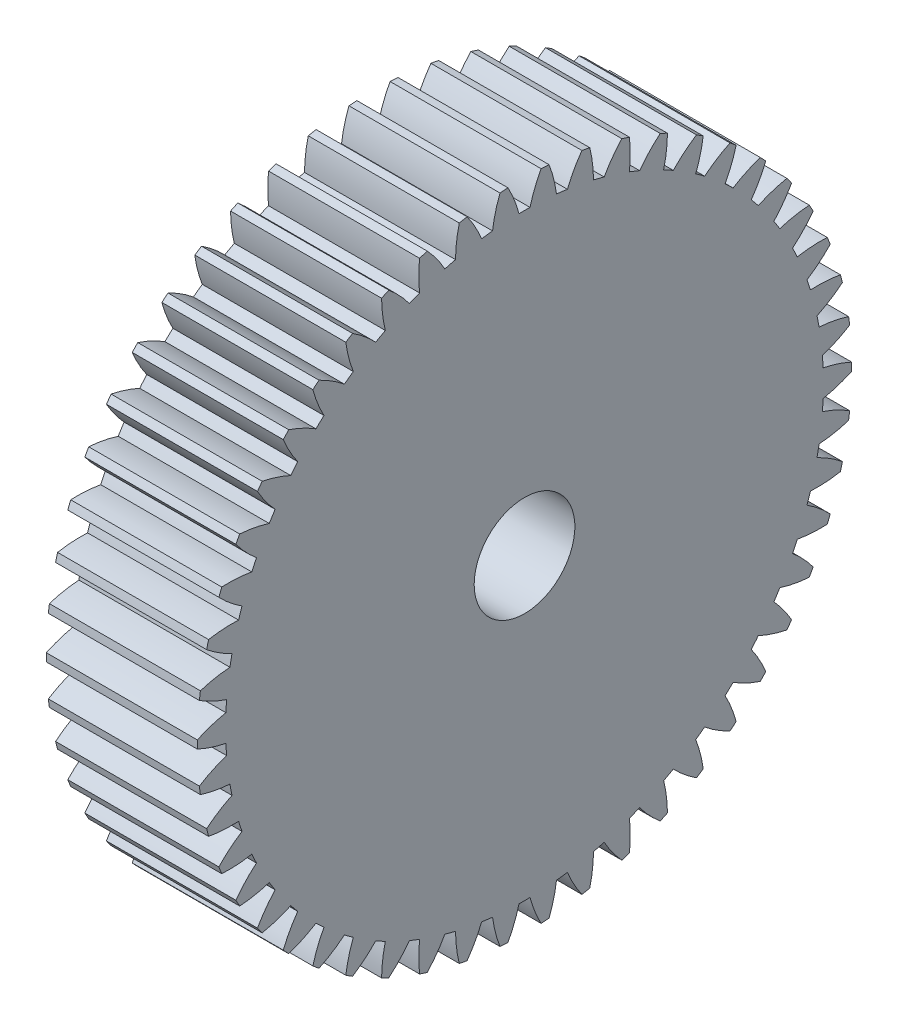
SolidWorks part; units mm, degrees
ref_plane "Plane1" through (0, 0, 0) normal (0, 0, 1) x (1, 0, 0)
ref_plane "Plane2" through (0, 0, 0) normal (0, 1, 0) x (1, 0, 0)
ref_plane "Plane3" through (0, 0, 0) normal (1, 0, 0) x (0, 0, -1)
sketch "HoldingSke" plane through (0, 0, 0) normal (0, 1, 0) x (1, 0, 0)
  line L0 (0, 0) -> (0.6428, -0.766)
  line L1 (-15, 0) -> (100, 0) construction
  line L2 (0, 0) -> (-2.1039, 2.3779)
  line L3 (0, 0) -> (-11.863, 4.5341)
  line L4 (0, 0) -> (5.5511, 6.6156)
  line L5 (0, 0) -> (-46.8476, -17.4728)
  line L6 (0, 0) -> (-9.9476, -6.7116)
  line L7 (-2.1039, 2.3779) -> (8.6586, 51.2059)
  line L8 (-76.2, 54.61) -> (-74.8, 54.61)
  line L9 (-71.009, 38.7566) -> (-53.1078, 45.2721)
  line L10 (-76.2, 71.12) -> (104.1128, 71.12)
  line L11 (0, 0) -> (-12, 0)
  line L12 (-76.2, 101.6) -> (-76.162, 101.6)
  line L13 (24.9733, 27.94) -> (52.9518, 28.4284)
  line L14 (24.9733, 27.94) -> (24.9743, 27.94)
  line L15 (24.9733, 27.94) -> (100.4006, 29.5858)
  line L16 (-63.627, -1) -> (-12.827, -1)
  circle A0 centre (0, 0) radius 4
  circle A1 centre (0, 0) radius 23.749
  circle A2 centre (0, 0) radius 37.5
  circle A3 centre (0, 0) radius 4
  dimension "MHD" = 47.498
  dimension "Hub_dia" = 75
  dimension "Bore" = 8
  dimension "MBD" = 8
  dimension "Num_teeth" = 50
  dimension "Pitch" = 1
  dimension "Overall_len" = 50
  dimension "Show_teeth" = 50
  dimension "Thickness" = 12
  dimension "OAL" = 50.0001
  dimension "T_dim" = 1.4
  dimension "Ap" = 20
  dimension "H" = 19.05
  dimension "Pitch_radius" = 180.3128
  dimension "Width" = 12
  dimension "Backlash" = 0.038
  dimension "Addendum_fac" = 1
  dimension "Dedendum_fac" = 1.25
  dimension "Clearance_fac" = 0.25
  dimension "Dedendum_add" = 0.001
  dimension "Module" = 1
sketch "BasProSke" plane through (0, 0, 0) normal (0, 1, 0) x (1, 0, 0)
  line L0 (-10, 0) -> (60, 0) construction
  line L1 (0, 0) -> (0, 26)
  line L2 (0, 0) -> (12, 0)
  line L3 (12, 0) -> (12, 26)
  line L4 (12, 26) -> (0, 26)
  dimension "Thickness" = 12
  dimension "Diameter" = 52
revolve "Base-Revolve" add sketch "BasProSke" angle 360 about L0
sketch "TooCutSke" plane through (0, 0, 0) normal (1, 0, 0) x (0, 0, -1)
  line L1 (0, 0) -> (0, 107) construction
  line L2 (0, 0) -> (-0.8518, 24.9855) construction
  line L3 (0, 0) -> (-3.1382, 49.8807) construction
  line L4 (-0.8518, 24.9855) -> (-1.5691, 24.9404) construction
  arc A0 (0.4377, 23.745) -> (-0.4377, 23.745) centre (0, 0) ccw
  arc A1 (1.3294, 25.9914) -> (-1.3294, 25.9914) centre (0, 0) ccw
  circle A2 centre (0, 0) radius 25 construction
  circle A3 centre (0, 0) radius 23.4923 construction
  arc A4 (-0.4377, 23.745) -> (-1.3294, 25.9914) centre (-10.1099, 21.2056) ccw
  arc A5 (1.3294, 25.9914) -> (0.4377, 23.745) centre (10.1099, 21.2056) ccw
  dimension "Root_dia" = 47.498
  dimension "Overcut_dia" = 52.0508
  dimension "Pitch_dia" = 50
  dimension "Base_dia" = 46.9846
  dimension "Flank_rad" = 10
  dimension "Half_ang" = 3.6
  dimension "Half_CT" = 0.7188
extrude "ToothCut" cut sketch "TooCutSke" along normal through all
fillet "Breaks" [suppressed] radius 0.02
fillet "RootFillets" [suppressed] radius 0.251
pattern_circular "TeethCuts" count 50 every 7.2 about axis through (-10, 0, 0) along (1, 0, 0) of "ToothCut", "RootFillets", "Breaks"
sketch "HubNeaOneSke" plane through (0, 0, 0) normal (-1, 0, 0) x (0, 0, 1)
  circle A0 centre (0, 0) radius 23.749
  dimension "Diameter" = 47.498
extrude "HubNearOne" [suppressed] add sketch "HubNeaOneSke" along normal blind 38.0001
sketch "HubNeaBotSke" plane through (0, 0, 0) normal (-1, 0, 0) x (0, 0, 1)
  circle A0 centre (0, 0) radius 23.749
  dimension "Diameter" = 47.498
extrude "HubNearBoth" [suppressed] add sketch "HubNeaBotSke" along normal blind 19
ref_plane "FarPln" through (12, 0, 0) normal (1, 0, 0) x (0, 0, -1)
sketch "HubFarSke" plane through (12, 0, 0) normal (1, 0, 0) x (0, 0, -1)
  circle A0 centre (0, 0) radius 23.749
  dimension "Diameter" = 47.498
extrude "HubFar" [suppressed] add sketch "HubFarSke" along normal blind 19
sketch "BorSke" plane through (0, 0, 0) normal (1, 0, 0) x (0, 0, -1)
  circle A0 centre (0, 0) radius 4
  dimension "Diameter" = 8
extrude "Bore" cut sketch "BorSke" along normal mid plane 100.0001
sketch "KeySke" plane through (0, 0, 0) normal (1, 0, 0) x (0, 0, -1)
  line L0 (-1, 0) -> (-1, 5.4)
  line L1 (-1, 5.4) -> (1, 5.4)
  line L2 (1, 5.4) -> (1, 0)
  line L3 (0, 0) -> (0, 34) construction
  line L4 (-1, 0) -> (1, 0)
  dimension "Offset" = 5.4
  dimension "Width" = 2
extrude "Keyway" [suppressed] cut sketch "KeySke" along normal mid plane 100.0001
pattern_circular "Keyway2" [suppressed] count 2 every 90 about axis through (-10, 0, 0) along (1, 0, 0)
equation "' \"Module@HoldingSke\" = 6.35"
equation "' \"Num_teeth@HoldingSke\" = 12"
equation "' \"Ap@HoldingSke\" =  20"
equation "' \"Ap@HoldingSke\" = 20"
equation "' \"Width@HoldingSke\" = 0.5 * 25.4"
equation "' \"Hub_dia@HoldingSke\"= 1 * 25.4"
equation "' \"Hub_dia@HoldingSke\" = 1 * 25.4"
equation "' \"Overall_len@HoldingSke\" = 1.0 * 25.4"
equation "' \"Bore@HoldingSke\" = 0.75 * 25.4"
equation "' \"T_dim@HoldingSke\" = 0.1 * 25.4"
equation "' \"Width@KeySke\" = 0.25 * 25.4"
equation "' \"Show_teeth@HoldingSke\" = 13"
equation "' \"Backlash@HoldingSke\" = 0.009 * 25.4"
equation "' \"Addendum_fac@HoldingSke\" = 1.0"
equation "' \"Dedendum_fac@HoldingSke\" = 1.25"
equation "' \"Dedendum_add@HoldingSke\" = 0.00005 * 25.4"
equation "' \"Clearance_fac@HoldingSke\" = 0.25"
equation "\"Pitch@HoldingSke\" = 1 / \"Module@HoldingSke\""
equation "\"Overcut_dia@TooCutSke\" = (\"Num_teeth@HoldingSke\" + 2 * \"Addendum_fac@HoldingSke\") / \"Pitch@HoldingSke\" + 0.002 * 25.4"
equation "\"Pitch_dia@TooCutSke\" = \"Num_teeth@HoldingSke\" / \"Pitch@HoldingSke\""
equation "\"Base_dia@TooCutSke\" = \"Num_teeth@HoldingSke\" / \"Pitch@HoldingSke\" * cos((\"Ap@HoldingSke\"  * 3.14159265 / 180))"
equation "\"Root_dia@TooCutSke\" = (\"Num_teeth@HoldingSke\" + 2) / \"Pitch@HoldingSke\" - 2 * (\"Addendum_fac@HoldingSke\" + \"Dedendum_fac@HoldingSke\") / \"Pitch@HoldingSke\" - \"Dedendum_add@HoldingSke\" * 2"
equation "\"Half_ang@TooCutSke\" = 180 / \"Num_teeth@HoldingSke\""
equation "\"Half_CT@TooCutSke\" = \"Num_teeth@HoldingSke\" / \"Pitch@HoldingSke\" * sin((3.14159265 / 2 / \"Num_teeth@HoldingSke\")) / 2 - 7 * \"Backlash@HoldingSke\" / 4"
equation "\"Flank_rad@TooCutSke\" = \"Num_teeth@HoldingSke\" / \"Pitch@HoldingSke\" / 5"
equation "\"Radius@RootFillets\" = \"Clearance_fac@HoldingSke\" / \"Pitch@HoldingSke\" + \"Dedendum_add@HoldingSke\""
equation "\"Break_rad@Breaks\" = 0.02 / \"Pitch@HoldingSke\""
equation "\"Thickness@HoldingSke\" = \"Width@HoldingSke\""
equation "\"OAL@HoldingSke\" = \"Thickness@HoldingSke\""
equation "\"MHD@HoldingSke\" = (\"Num_teeth@HoldingSke\" + 2) / \"Pitch@HoldingSke\" - 2 * (\"Addendum_fac@HoldingSke\" + \"Dedendum_fac@HoldingSke\")  / \"Pitch@HoldingSke\" - \"Dedendum_add@HoldingSke\" * 2"
equation "\"MBD@HoldingSke\" = (\"Num_teeth@HoldingSke\" + 2) / \"Pitch@HoldingSke\" - 2 * (\"Addendum_fac@HoldingSke\" + \"Dedendum_fac@HoldingSke\")  / \"Pitch@HoldingSke\" - \"Dedendum_add@HoldingSke\" * 2 - 0.002 * 25.4"
equation "\"MHD@HoldingSke\" = ((sgn( \"MHD@HoldingSke\" - \"Hub_dia@HoldingSke\" )-1)*( \"MHD@HoldingSke\" - \"Hub_dia@HoldingSke\" ))/-2+ \"Hub_dia@HoldingSke\""
equation "\"MBD@HoldingSke\" = ((sgn( \"MBD@HoldingSke\" - \"Bore@HoldingSke\" )-1)*( \"MBD@HoldingSke\" - \"Bore@HoldingSke\" ))/-2+ \"Bore@HoldingSke\""
equation "\"OAL@HoldingSke\" = ((sgn( \"OAL@HoldingSke\" - \"Overall_len@HoldingSke\" )+1)*( \"OAL@HoldingSke\" - \"Overall_len@HoldingSke\" ))/2 + \"Overall_len@HoldingSke\" + 0.000002 * 25.4"
equation "\"Num_teeth@TeethCuts\" = int( \"Show_teeth@HoldingSke\" ) + 1"
equation "\"Num_teeth@TeethCuts\" = ((sgn( \"Num_teeth@TeethCuts\" - \"Num_teeth@HoldingSke\" )-1)*( \"Num_teeth@TeethCuts\" - \"Num_teeth@HoldingSke\" ))/-2+ \"Num_teeth@HoldingSke\""
equation "\"Num_teeth@TeethCuts\" = ((sgn( \"Num_teeth@TeethCuts\" - 2.0)+1)*( \"Num_teeth@TeethCuts\" - 2.0))/2 +2.0"
equation "\"Angle@TeethCuts\" = 360.0 / \"Num_teeth@HoldingSke\""
equation "\"Diameter@BasProSke\" = (\"Num_teeth@HoldingSke\" + 2 * \"Addendum_fac@HoldingSke\") / \"Pitch@HoldingSke\""
equation "\"Thickness@BasProSke\"  = \"Thickness@HoldingSke\""
equation "' \"Fillet_rad@BasProSke\" =  \"Thickness@HoldingSke\" * 0.05"
equation "' \"Fillet_rad@BasProSke\" = \"Thickness@HoldingSke\" * 0.05"
equation "\"MHD@HoldingSke\" = ((sgn( \"MHD@HoldingSke\" - \"Root_dia@TooCutSke\" )-1)*( \"MHD@HoldingSke\" - \"Root_dia@TooCutSke\" ))/-2+ \"Root_dia@TooCutSke\""
equation "\"Diameter@HubNeaOneSke\" = \"MHD@HoldingSke\""
equation "\"Length@HubNearOne\" = \"OAL@HoldingSke\" - \"Thickness@BasProSke\""
equation "\"Diameter@HubNeaBotSke\" = \"MHD@HoldingSke\""
equation "\"Length@HubNearBoth\" = ( \"OAL@HoldingSke\" - \"Thickness@BasProSke\" ) / 2.0"
equation "\"Thickness@FarPln\" = \"Thickness@BasProSke\""
equation "\"Diameter@HubFarSke\" = \"MHD@HoldingSke\""
equation "\"Length@HubFar\" = ( \"OAL@HoldingSke\" - \"Thickness@BasProSke\" ) / 2.0"
equation "\"Diameter@BorSke\" = \"MBD@HoldingSke\""
equation "\"D1@Bore\" = \"OAL@HoldingSke\" * 2.0"
equation "\"D1@Keyway\" = \"OAL@HoldingSke\" * 2.0"
equation "\"Offset@KeySke\" = \"T_dim@HoldingSke\" + \"MBD@HoldingSke\" / 2.0"
